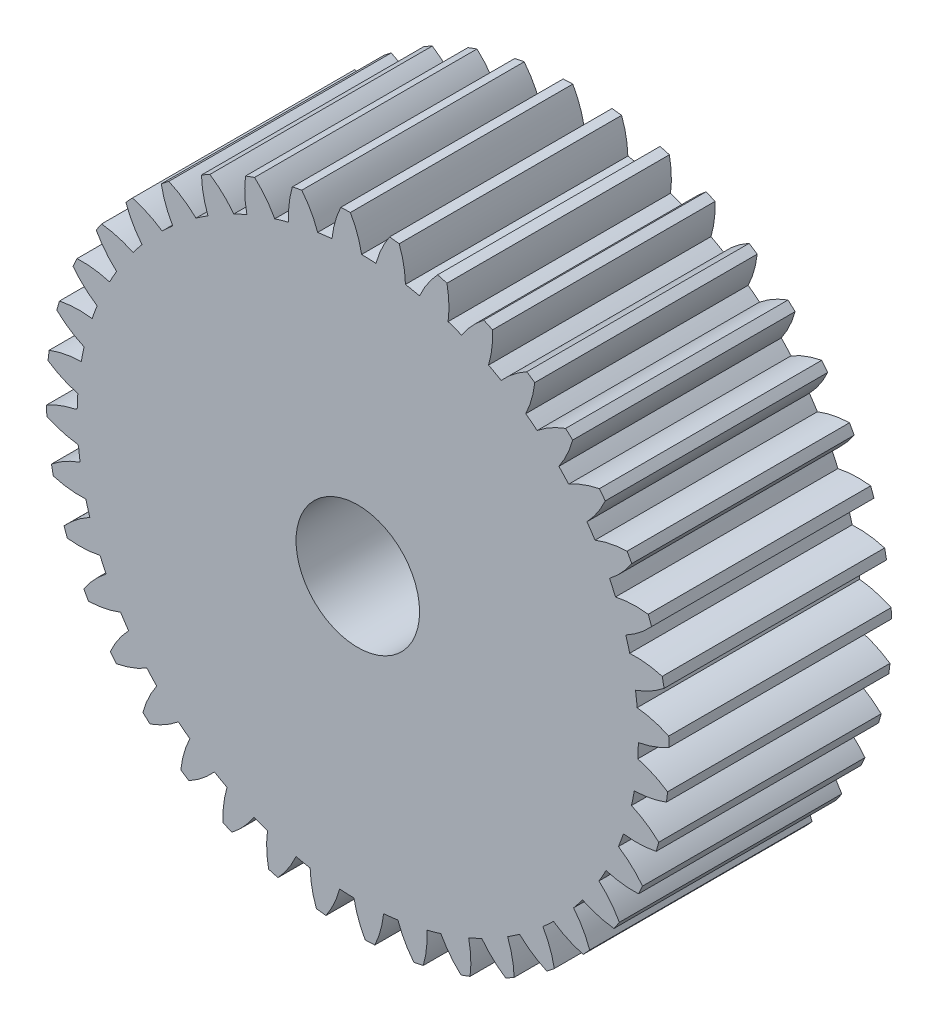
SolidWorks part; units mm, degrees
ref_plane "Front Plane" through (0, 0, 0) normal (0, 0, 1) x (1, 0, 0)
ref_plane "Top Plane" through (0, 0, 0) normal (0, 1, 0) x (1, 0, 0)
ref_plane "Right Plane" through (0, 0, 0) normal (1, 0, 0) x (0, 0, -1)
sketch "Sketch2" plane through (0, 0, 0) normal (0, 0, 1) x (1, 0, 0)
  line L0 (-60, 0) -> (-60, 24.0946)
  line L1 (-60, 0) -> (-50.5388, 25.9945)
  line L2 (-56.3816, 0) -> (-63, 0) construction
  line L3 (-56.3816, 0) -> (-59.6908, 0)
  line L4 (-59.6908, 0) -> (-63, 0)
  line L5 (-59.6908, 0) -> (-53.2558, -18.5122) construction
  line L6 (-59.6908, 0) -> (-57.5458, -6.1707)
  line L7 (-57.5458, -6.1707) -> (-55.4008, -12.3414)
  line L8 (-55.4008, -12.3414) -> (-53.2558, -18.5122)
  line L9 (-53.2558, -18.5122) -> (-51.1108, -24.6829)
  line L10 (0, 0) -> (-62.9514, -2.4734) construction
  line L11 (0, 0) -> (-59.6908, 0) construction
  circle A0 centre (0, 0) radius 60
  circle A1 centre (0, 0) radius 56.7644
  circle A2 centre (0, 0) radius 63
  circle A3 centre (0, 0) radius 56.3816
  arc A4 (-62.9822, -1.4973) -> (-56.7592, 0.7709) centre (-53.2558, -18.5122) cw
  arc A5 (-62.9055, -3.4489) -> (-56.5237, -5.2218) centre (-54.5441, 14.2767) ccw
  dimension "D1" = 120
  dimension "D2" = 126
  dimension "D3" = 113.5288
  dimension "D4" = 20
  dimension "D6" = 2.25
sketch "Sketch5" plane through (0, 0, 0) normal (0, 0, 1) x (1, 0, 0)
  arc A0 (-56.7592, 0.7709) -> (-62.9822, -1.4973) centre (-53.2558, -18.5122) ccw construction
  arc A1 (-56.7592, 0.7709) -> (-62.9822, -1.4973) centre (-53.2558, -18.5122) ccw
  arc A2 (-62.9055, -3.4489) -> (-56.5237, -5.2218) centre (-54.5441, 14.2767) ccw construction
  arc A3 (-62.9055, -3.4489) -> (-56.5237, -5.2218) centre (-54.5441, 14.2767) ccw
  circle A4 centre (0, 0) radius 56.7644 construction
  circle A5 centre (0, 0) radius 63 construction
  arc A6 (-56.7592, 0.7709) -> (-56.5237, -5.2218) centre (0, 0) ccw
  arc A7 (-62.9822, -1.4973) -> (-62.9055, -3.4489) centre (0, 0) ccw
extrude "Boss-Extrude3" add sketch "Sketch5" along normal blind 45
extrude "Boss-Extrude4" add sketch "Sketch2" along normal blind 45 contours A1
fillet "Fillet1" radius 0.5 1 edges at (-56.7592, 0.7709, 22.5)
fillet "Fillet3" radius 0.5 1 edges at (-56.5237, -5.2218, 22.5)
sketch "Sketch6" plane through (0, 0, 45) normal (0, 0, 1) x (1, 0, 0)
  circle A0 centre (0, 0) radius 12.5
  dimension "D1" = 25
pattern_circular "CirPattern1" count 40 over 360 about axis through (0, 0, 0) along (0, 0, 1) of "Boss-Extrude3"
extrude "Cut-Extrude1" cut sketch "Sketch6" against normal blind 45
equation "\"Teeth\"= 40"
equation "\"Module\"= 3"
equation "\"pcd\"= \"Teeth\" * \"Module\""
equation "\"circularpitch\"= 3.1415 * \"Module\""
equation "\"diametricalpitch\"= 1 / \"Module\""
equation "\"addendum\"= \"Module\""
equation "\"addendumCircularDiameter\"= \"pcd\" + 2 * \"Module\""
equation "\"clearance\"= \"circularpitch\" / \"Teeth\""
equation "\"dedendum\"= \"addendum\" + \"clearance\""
equation "\"dedendumCircularDiameter\"= \"pcd\" - 2 * \"dedendum\""
equation "\"pressureangle\"= 20"
equation "\"circularpitchangle\"= \"circularpitch\" * 360 / ( 3.1415 * \"pcd\" * 4 )"
equation "\"D2@Sketch2\"=\"addendumCircularDiameter\""
equation "\"D1@Sketch2\"=\"pcd\""
equation "\"D3@Sketch2\"=\"dedendumCircularDiameter\""
equation "\"D4@Sketch2\"=\"pressureangle\""
equation "\"D6@Sketch2\"=\"circularpitchangle\""
equation "\"D1@CirPattern1\"=\"Teeth\""
